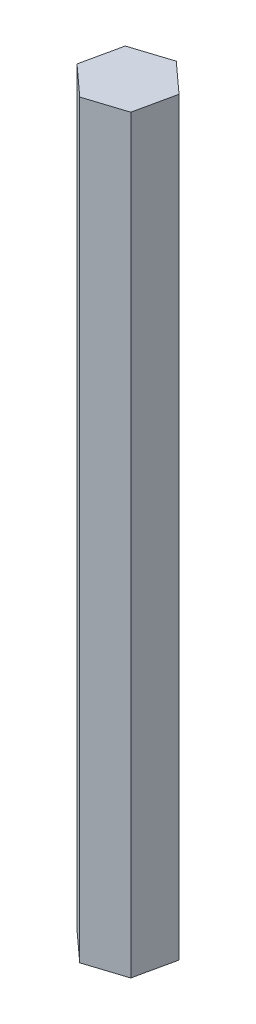
SolidWorks part; units mm, degrees
ref_plane "Front Plane" through (0, 0, 0) normal (0, 0, 1) x (1, 0, 0)
ref_plane "Top Plane" through (0, 0, 0) normal (0, 1, 0) x (1, 0, 0)
ref_plane "Right Plane" through (0, 0, 0) normal (1, 0, 0) x (0, 0, -1)
sketch "Sketch2" plane through (0, 0, 0) normal (0, 1, 0) x (1, 0, 0)
  line L1 (2.1373, -1.9404) -> (2.7491, 0.8807)
  line L2 (2.7491, 0.8807) -> (0.6118, 2.8212)
  line L3 (0.6118, 2.8212) -> (-2.1373, 1.9404)
  line L4 (-2.1373, 1.9404) -> (-2.7491, -0.8807)
  line L5 (-2.7491, -0.8807) -> (-0.6118, -2.8212)
  line L6 (-0.6118, -2.8212) -> (2.1373, -1.9404)
  circle A0 centre (0, 0) radius 2.5 construction
extrude "Boss-Extrude1" add sketch "Sketch2" along normal blind 53.34
